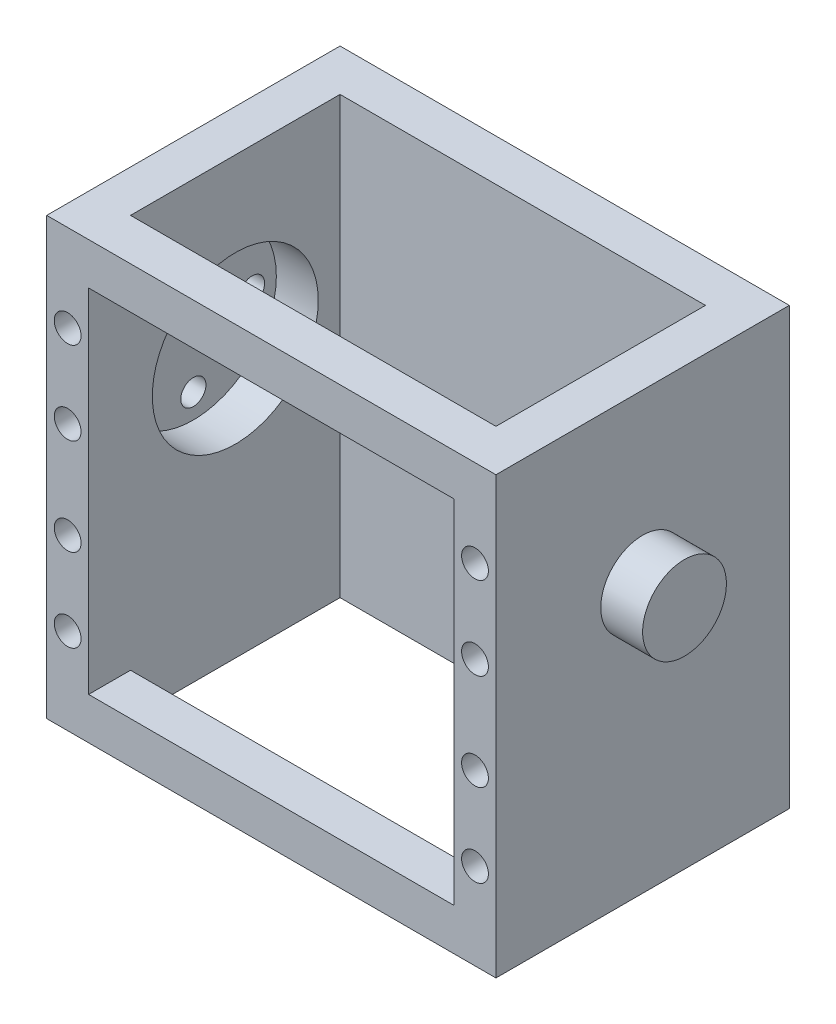
SolidWorks part; units mm, degrees
ref_plane "Front Plane" through (0, 0, 0) normal (0, 0, 1) x (1, 0, 0)
ref_plane "Top Plane" through (0, 0, 0) normal (0, 1, 0) x (1, 0, 0)
ref_plane "Right Plane" through (0, 0, 0) normal (1, 0, 0) x (0, 0, -1)
sketch "Sketch1" plane through (0, 0, 0) normal (0, 1, 0) x (1, 0, 0)
  line L1 (0, 0) -> (53.6, 0)
  line L2 (0, 0) -> (0, -35)
  line L3 (0, -35) -> (53.6, -35)
  line L4 (53.6, 0) -> (53.6, -35)
  line L5 (5, -5) -> (48.6, -5)
  line L6 (5, -5) -> (5, -30)
  line L7 (5, -30) -> (48.6, -30)
  line L8 (48.6, -5) -> (48.6, -30)
  dimension "D1" = 35
  dimension "D2" = 5
  dimension "D3" = 43.6
  dimension "D4" = 5
  dimension "D5" = 25
  dimension "D6" = 5
extrude "Boss-Extrude1" add sketch "Sketch1" along normal blind 52
sketch "Sketch2" plane through (0, 0, 35) normal (0, 0, 1) x (1, 0, 0)
  line L0 (0, 52) -> (0, 0) construction
  line L1 (5, 47) -> (48.6, 47)
  line L2 (5, 47) -> (5, 5)
  line L3 (5, 5) -> (48.6, 5)
  line L4 (48.6, 47) -> (48.6, 5)
  line L5 (53.6, 52) -> (53.6, 0) construction
  line L6 (0, 0) -> (53.6, 0) construction
  dimension "D1" = 5
  dimension "D2" = 5
  dimension "D3" = 5
  dimension "D4" = 42
extrude "Cut-Extrude1" cut sketch "Sketch2" against normal blind 5
sketch "Sketch3" plane through (0, 0, 35) normal (0, 0, 1) x (1, 0, 0)
  line L0 (6.8, 25.5) -> (46.8, 25.5)
  line L1 (6.8, 25.5) -> (6.8, 5)
  line L2 (6.8, 5) -> (46.8, 5)
  line L3 (46.8, 25.5) -> (46.8, 5)
  line L4 (6.8, 15.25) -> (46.8, 15.25) construction
  line L5 (26.8, 25.5) -> (26.8, 5) construction
  line L6 (5, 5) -> (48.6, 5) construction
  line L7 (0, 52) -> (0, 0) construction
  line L8 (53.6, 60.3238) -> (53.6, -14.2444) construction
  line L9 (6.8, 46.9) -> (46.8, 46.9)
  line L10 (6.8, 46.9) -> (6.8, 26.4)
  line L11 (6.8, 26.4) -> (46.8, 26.4)
  line L12 (46.8, 46.9) -> (46.8, 26.4)
  line L13 (6.8, 36.65) -> (46.8, 36.65) construction
  line L14 (26.8, 46.9) -> (26.8, 26.4) construction
  line L15 (53.6, 81.7238) -> (53.6, 7.1556) construction
  circle A0 centre (51.1, 20.2) radius 1.6
  circle A1 centre (51.1, 10.3) radius 1.6
  circle A2 centre (2.5, 10.3) radius 1.6
  circle A3 centre (2.5, 20.2) radius 1.6
  circle A4 centre (51.1, 41.6) radius 1.6
  circle A5 centre (51.1, 31.7) radius 1.6
  circle A6 centre (2.5, 31.7) radius 1.6
  circle A7 centre (2.5, 41.6) radius 1.6
  dimension "D3" = 3.2
  dimension "D4" = 3.2
  dimension "D5" = 3.2
  dimension "D6" = 3.2
  dimension "D21" = 3.2
  dimension "D22" = 3.2
  dimension "D23" = 3.2
  dimension "D24" = 3.2
  dimension "D1" = 40
  dimension "D2" = 20.5
  dimension "D7" = 9.9
  dimension "D8" = 9.9
  dimension "D9" = 48.6
  dimension "D10" = 48.6
  dimension "D11" = 24.3
  dimension "D12" = 24.3
  dimension "D13" = 24.3
  dimension "D14" = 5.3
  dimension "D15" = 0
  dimension "D16" = 2.5
  dimension "D17" = 2.5
  dimension "D18" = 53.6
  dimension "D19" = 40
  dimension "D20" = 20.5
  dimension "D25" = 9.9
  dimension "D26" = 9.9
  dimension "D27" = 48.6
  dimension "D28" = 48.6
  dimension "D29" = 24.3
  dimension "D30" = 24.3
  dimension "D31" = 24.3
  dimension "D32" = 5.3
  dimension "D33" = 2.5
  dimension "D34" = 2.5
  dimension "D35" = 11.5
extrude "Cut-Extrude2" cut sketch "Sketch3" against normal blind 5
sketch "Sketch4" plane through (53.6, 0, 0) normal (1, 0, 0) x (0, 0, -1)
  line L0 (-35, 52) -> (0, 52) construction
  line L1 (0, 52) -> (0, 0) construction
  line L2 (-35, 52) -> (-35, 0) construction
  circle A0 centre (-17.5, 32) radius 9.9
  circle A1 centre (-17.5, 39) radius 1.5
  circle A2 centre (-10.5, 32) radius 1.5
  circle A3 centre (-17.5, 25) radius 1.5
  circle A4 centre (-24.5, 32) radius 1.5
  circle A5 centre (-17.5, 32) radius 1.5
  dimension "D1" = 3
  dimension "D2" = 3
  dimension "D3" = 3
  dimension "D4" = 3
  dimension "D5" = 3
  dimension "D6" = 19.8
  dimension "D11" = 20
  dimension "D7" = 14
  dimension "D8" = 7
  dimension "D9" = 14
  dimension "D10" = 7
  dimension "D12" = 17.5
  dimension "D13" = 17.5
sketch "Sketch7" plane through (0, 0, 0) normal (-1, 0, 0) x (0, 0, 1)
  line L0 (0, 52) -> (0, 0) construction
  line L1 (0, 52) -> (35, 52) construction
  circle A0 centre (17.5, 32) radius 9.9
  circle A1 centre (17.5, 39) radius 1.5
  circle A2 centre (24.5, 32) radius 1.5
  circle A3 centre (17.5, 25) radius 1.5
  circle A4 centre (10.5, 32) radius 1.5
  circle A5 centre (17.5, 32) radius 1.5
  dimension "D1" = 3
  dimension "D2" = 3
  dimension "D3" = 3
  dimension "D4" = 3
  dimension "D5" = 3
  dimension "D6" = 19.8
  dimension "D7" = 14
  dimension "D8" = 7
  dimension "D9" = 14
  dimension "D10" = 7
  dimension "D11" = 17.5
  dimension "D12" = 20
extrude "Boss-Extrude4" add sketch "Sketch7" along normal blind 3
sketch "Sketch8" plane through (5, 0, 0) normal (1, 0, 0) x (0, 0, -1)
  circle A0 centre (-17.5, 32) radius 9.9
  dimension "D1" = 19.8
extrude "Cut-Extrude4" cut sketch "Sketch8" against normal blind 5
sketch "Sketch9" plane through (53.6, 0, 0) normal (1, 0, 0) x (0, 0, -1)
  circle A0 centre (-17.5, 32) radius 5
  dimension "D1" = 10
extrude "Boss-Extrude5" add sketch "Sketch9" along normal blind 5
